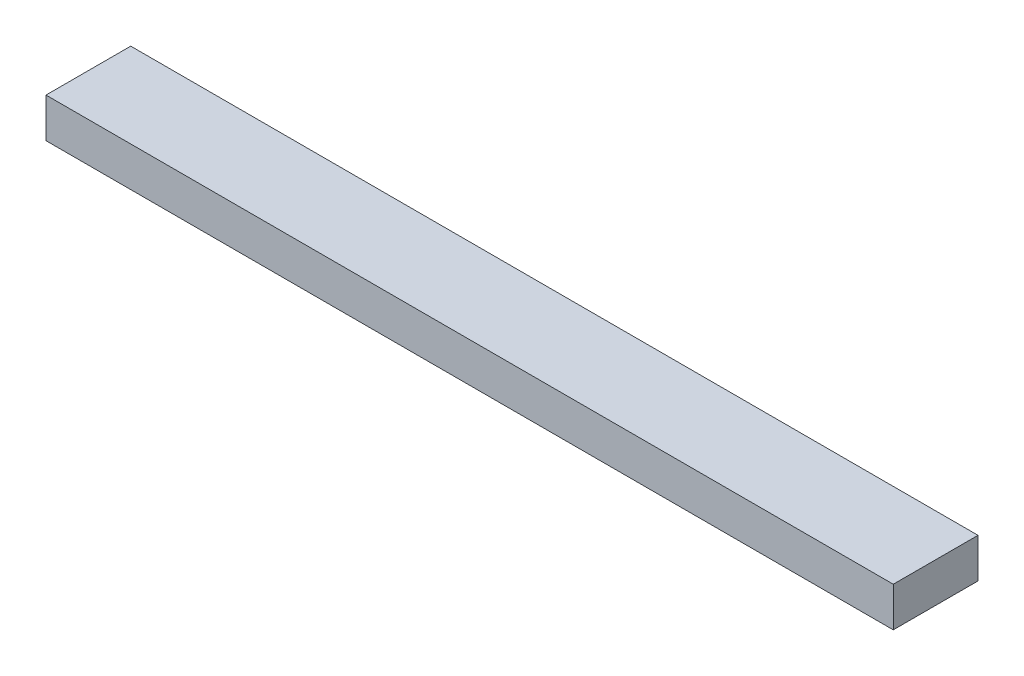
SolidWorks part; units mm, degrees
ref_plane "Front" through (0, 0, 0) normal (0, 0, 1) x (1, 0, 0)
ref_plane "Top" through (0, 0, 0) normal (0, 1, 0) x (1, 0, 0)
ref_plane "Right" through (0, 0, 0) normal (1, 0, 0) x (0, 0, -1)
sketch "Sketch1" plane through (0, 0, 0) normal (0, 0, 1) x (1, 0, 0)
  line L0 (0, 24.0952) -> (0, -55.3333) construction
  line L1 (-750, 0) -> (750, 0)
  line L2 (-750, 0) -> (-750, -70)
  line L3 (-750, -70) -> (750, -70)
  line L4 (750, 0) -> (750, -70)
  line L5 (547.1429, -35) -> (755.5238, -35) construction
  dimension "D1" = 70
  dimension "D2" = 1500
extrude "Boss-Extrude1" add sketch "Sketch1" along normal blind 150
